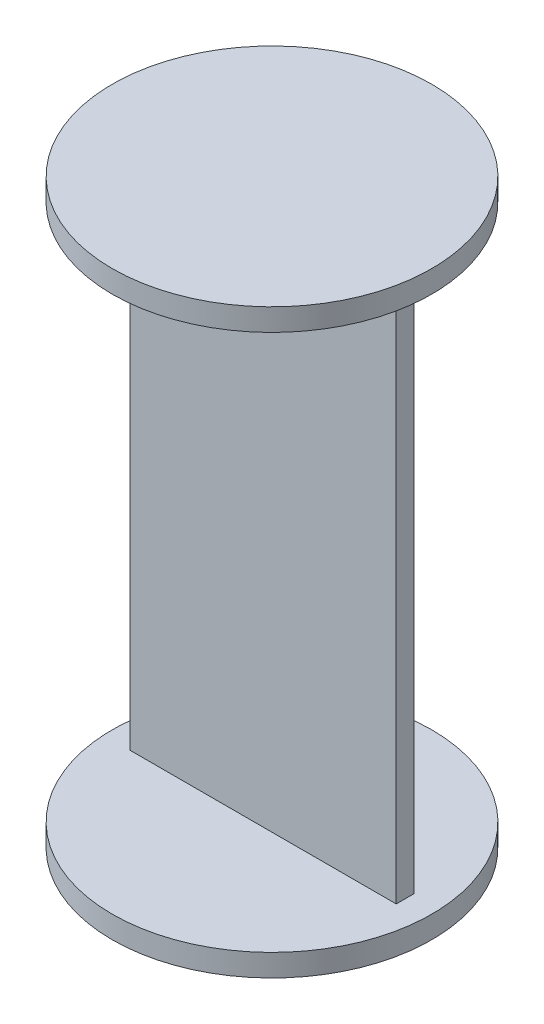
SolidWorks part; units mm, degrees
ref_plane "Front Plane" through (0, 0, 0) normal (0, 0, 1) x (1, 0, 0)
ref_plane "Top Plane" through (0, 0, 0) normal (0, 1, 0) x (1, 0, 0)
ref_plane "Right Plane" through (0, 0, 0) normal (1, 0, 0) x (0, 0, -1)
sketch "Sketch1" plane through (0, 0, 0) normal (0, 1, 0) x (1, 0, 0)
  circle A0 centre (0, 0) radius 45.72
  dimension "D1" = 91.44
extrude "Boss-Extrude1" add sketch "Sketch1" along normal blind 6.35
sketch "Sketch2" plane through (0, 6.35, 0) normal (0, 1, 0) x (1, 0, 0)
  line L1 (-38.1, 2.54) -> (38.1, 2.54)
  line L2 (-38.1, 2.54) -> (-38.1, -2.54)
  line L3 (-38.1, -2.54) -> (38.1, -2.54)
  line L4 (38.1, 2.54) -> (38.1, -2.54)
  point P4 (-38.1, 0)
  point P5 (0, 2.54)
  dimension "D1" = 76.2
  dimension "D2" = 5.08
extrude "Boss-Extrude4" add sketch "Sketch2" along normal blind 153.67
sketch "Sketch4" plane through (0, 160.02, 0) normal (0, 1, 0) x (1, 0, 0)
  circle A0 centre (0, 0) radius 45.72
extrude "Boss-Extrude5" add sketch "Sketch4" along normal blind 6.35
